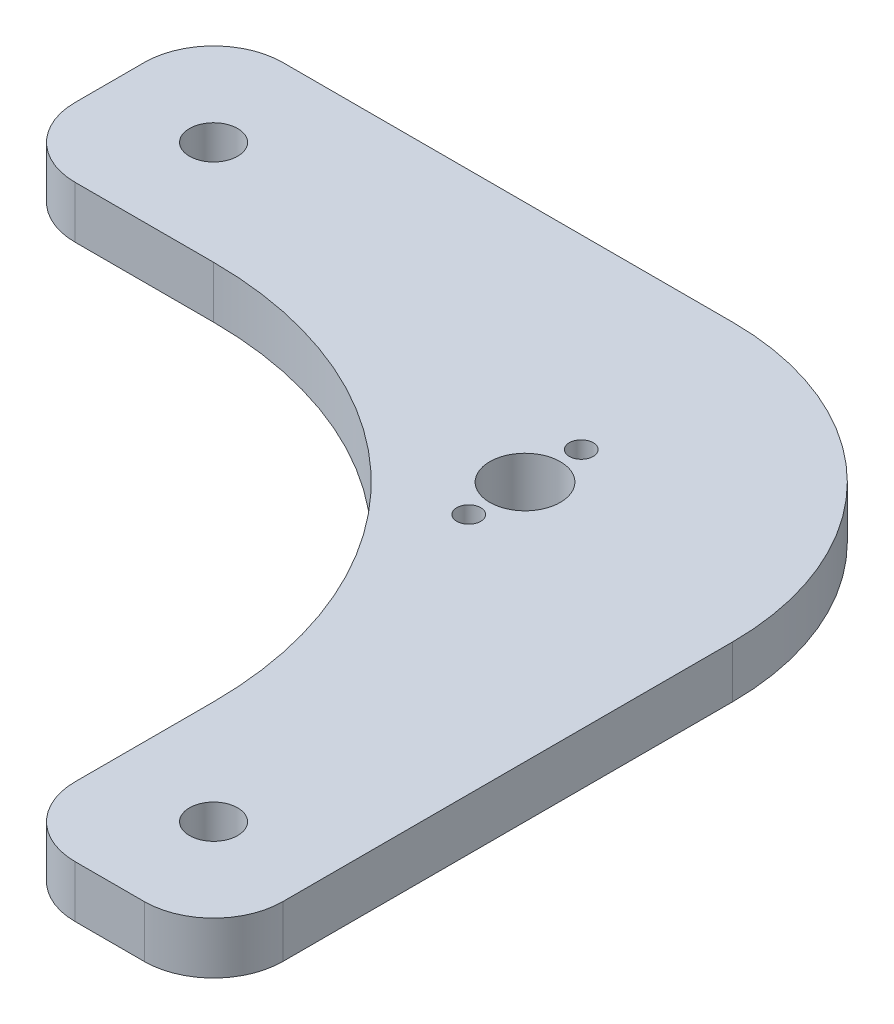
SolidWorks part; units mm, degrees
material "Acrylic (Medium-high impact)"
ref_plane "Front Plane" through (0, 0, 0) normal (0, 0, 1) x (1, 0, 0)
ref_plane "Top Plane" through (0, 0, 0) normal (0, 1, 0) x (1, 0, 0)
ref_plane "Right Plane" through (0, 0, 0) normal (1, 0, 0) x (0, 0, -1)
sketch "Sketch1" plane through (0, 0, 0) normal (0, 1, 0) x (1, 0, 0)
  line L0 (0, 146.05) -> (0, 0)
  line L1 (0, 0) -> (146.05, 0)
  line L2 (0, 146.05) -> (146.05, 146.05)
  line L3 (146.05, 146.05) -> (146.05, 0)
  dimension "D1" = 146.05
extrude "Boss-Extrude1" add sketch "Sketch1" along normal mid plane 9.525
sketch "Sketch2" plane through (0, 4.7625, 0) normal (0, 1, 0) x (1, 0, 0)
  line L0 (101.6, 91.2812) -> (101.6, 111.9188) construction
  line L1 (0, 0) -> (101.6, 0) construction
  line L2 (0, 0) -> (0, 101.6) construction
  line L3 (0, 101.6) -> (101.6, 101.6) construction
  line L4 (101.6, 0) -> (101.6, 101.6) construction
  circle A0 centre (101.6, 101.6) radius 6.477
  circle A1 centre (101.6, 91.2812) radius 2.1908
  circle A2 centre (101.6, 111.9188) radius 2.1908
  point P10 (101.6, 93.472)
  point P11 (101.6, 109.728)
  point P13 (101.6, 101.6)
  dimension "D1" = 12.954
  dimension "D3" = 4.3815
  dimension "D2" = 101.6
  dimension "D4" = 10.3187
extrude "Cut-Extrude1" cut sketch "Sketch2" against normal through all
hole_wizard "S (0.348) Diameter Hole1" positions "Sketch3" profile "Sketch4" hole size "S" standard "ANSI Inch" end condition through all
sketch "Sketch3" plane through (0, 4.7625, 0) normal (0, 1, 0) x (1, 0, 0)
  line L1 (19.05, 127) -> (127, 127) construction
  line L2 (19.05, 127) -> (19.05, 19.05) construction
  line L3 (19.05, 19.05) -> (127, 19.05) construction
  line L4 (127, 127) -> (127, 19.05) construction
  line L5 (0, 0) -> (146.05, 0) construction
  line L6 (0, 146.05) -> (0, 0) construction
  line L7 (146.05, 146.05) -> (0, 146.05) construction
  line L8 (0, 0) -> (146.05, 0) construction
  line L9 (0, 146.05) -> (0, 0) construction
  point P1 (19.05, 127)
  point P2 (127, 19.05)
  point P139 (57.15, 19.05)
  point P141 (19.05, 57.15)
  dimension "D1" = 19.05
  dimension "D2" = 19.05
  dimension "D3" = 19.05
  dimension "D4" = 57.15
  dimension "D5" = 57.15
sketch "Sketch4" plane through (19.05, 4.7625, -127) normal (1, 0, 0) x (0, 0, 1)
  line L0 (0, 0) -> (0, 9.525)
  line L1 (0, 9.525) -> (4.4196, 9.525)
  line L2 (4.4196, 9.525) -> (4.4196, 0)
  line L5 (4.4196, 0) -> (0, 0)
  line L11 (0, -6.35) -> (0, 107.95) construction
  dimension "Thru Hole Dia." = 8.8392
  dimension "Thru Hole Depth" = 9.525
sketch "Sketch5" plane through (0, 4.7625, 0) normal (0, 1, 0) x (1, 0, 0)
  line L0 (146.05, 146.05) -> (0, 146.05) construction
  line L1 (0, 107.95) -> (38.1, 107.95)
  line L2 (107.95, 0) -> (107.95, 38.1)
  line L3 (0, 0) -> (146.05, 0) construction
  line L4 (0, 107.95) -> (0, 0)
  line L5 (0, 0) -> (107.95, 0)
  line L6 (146.05, 0) -> (146.05, 146.05) construction
  arc A0 (38.1, 107.95) -> (107.95, 38.1) centre (38.1, 38.1) cw
  point P3 (0, 107.95)
  dimension "D1" = 38.1
  dimension "D2" = 38.1
  dimension "D3" = 38.1
  dimension "D4" = 38.1
extrude "Cut-Extrude2" cut sketch "Sketch5" against normal through all
fillet "Fillet1" radius 12.7 4 edges at (0, 0, -146.05) (146.05, 0, 0) (107.95, 0, 0) (0, 0, -107.95)
fillet "Fillet2" radius 50.8 1 edges at (146.05, 0, -146.05)
